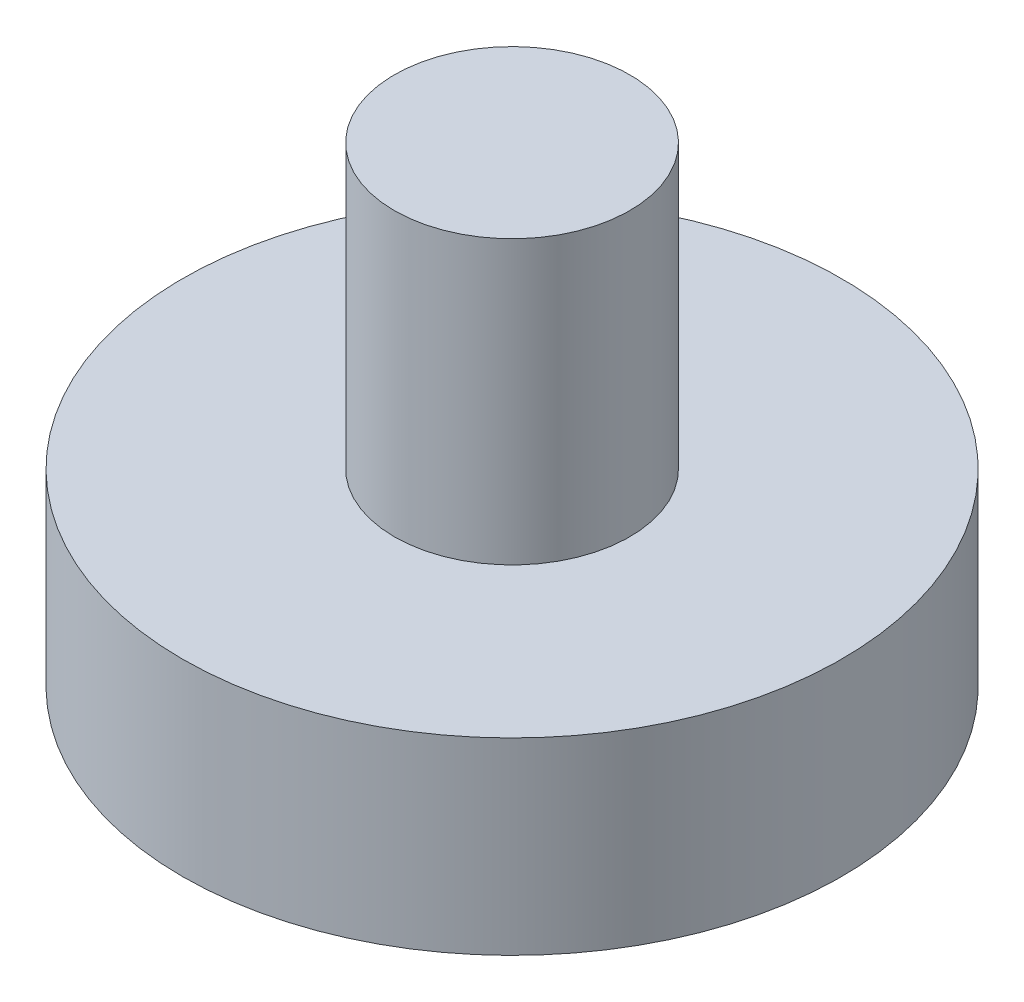
SolidWorks part; units mm, degrees
ref_plane "Front Plane" through (0, 0, 0) normal (0, 0, 1) x (1, 0, 0)
ref_plane "Top Plane" through (0, 0, 0) normal (0, 1, 0) x (1, 0, 0)
ref_plane "Right Plane" through (0, 0, 0) normal (1, 0, 0) x (0, 0, -1)
sketch "Sketch1" plane through (0, 0, 0) normal (0, 1, 0) x (1, 0, 0)
  circle A0 centre (0, 0) radius 3.5
  dimension "D1" = 7
extrude "Boss-Extrude1" add sketch "Sketch1" along normal blind 2
sketch "Sketch2" plane through (0, 2, 0) normal (0, 1, 0) x (1, 0, 0)
  circle A0 centre (0, 0) radius 1.25
  dimension "D1" = 2.5
extrude "Boss-Extrude2" add sketch "Sketch2" along normal blind 3
